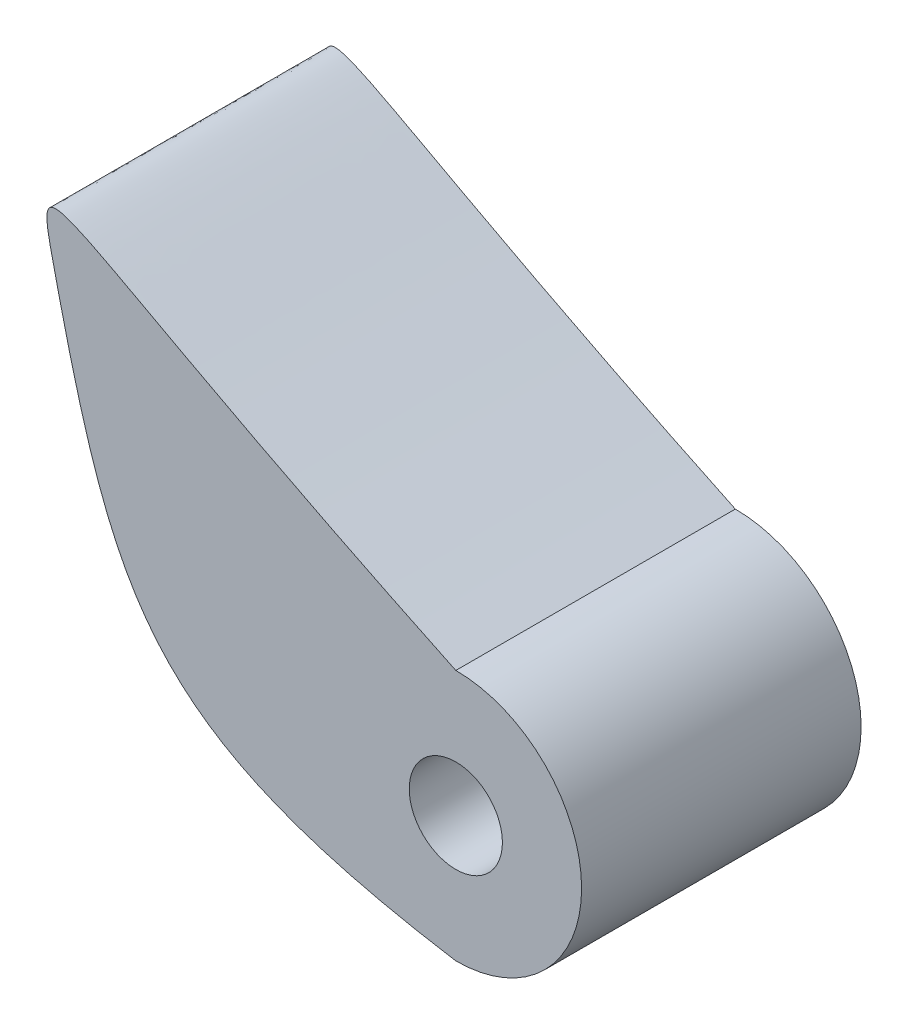
SolidWorks part; units mm, degrees
ref_plane "Plan de face" through (0, 0, 0) normal (0, 0, 1) x (1, 0, 0)
ref_plane "Plan de dessus" through (0, 0, 0) normal (0, 1, 0) x (1, 0, 0)
ref_plane "Plan de droite" through (0, 0, 0) normal (1, 0, 0) x (0, 0, -1)
sketch "Esquisse1" plane through (0, 0, 0) normal (0, 0, 1) x (1, 0, 0)
  circle A0 centre (0, 0) radius 2.5
  circle A1 centre (0, 0) radius 6.75
  spline S0 degree 3 poles (0, -6.75) (-12.8411, -4.6648) (-18.2184, 0.1016) (-23.1139, 21.4668) (-22.1621, 17.2865) (0, 6.75) knots 0 0 0 0 0.428894 0.581534 1 1 1 1
  dimension "D1" = 5
  dimension "D2" = 13.5
extrude "Boss.-Extru.2" add sketch "Esquisse1" against normal blind 15 contours S0 A1 A0 | S0 A1
